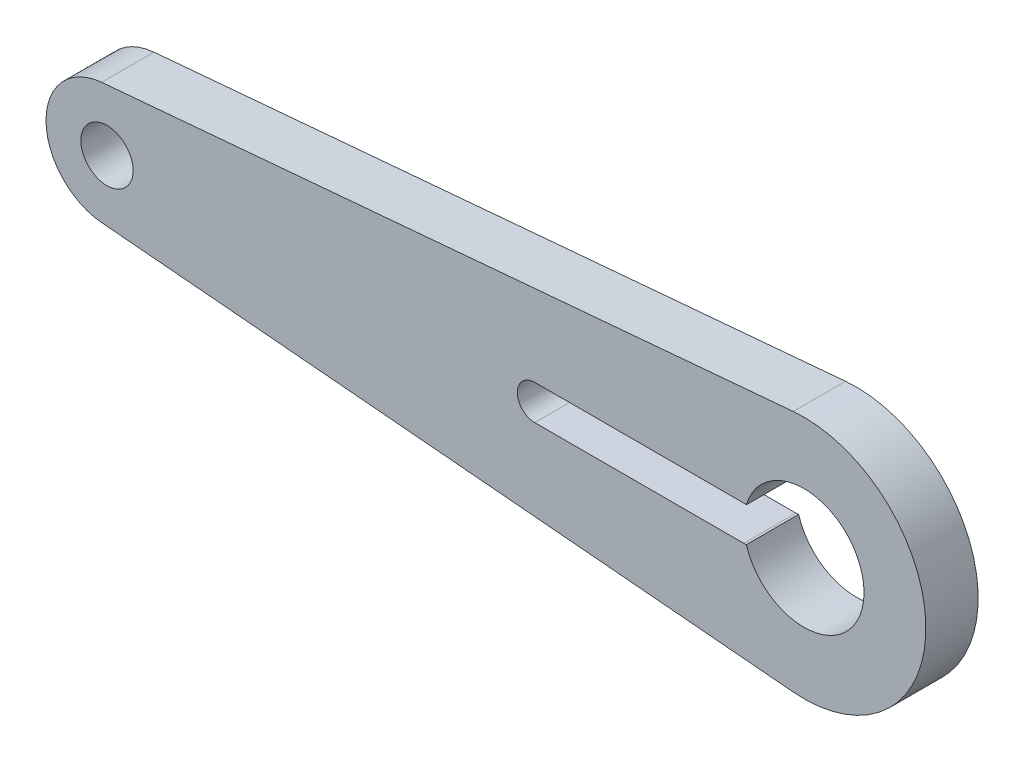
SolidWorks part; units mm, degrees
ref_plane "Front Plane" through (0, 0, 0) normal (0, 0, 1) x (1, 0, 0)
ref_plane "Top Plane" through (0, 0, 0) normal (0, 1, 0) x (1, 0, 0)
ref_plane "Right Plane" through (0, 0, 0) normal (1, 0, 0) x (0, 0, -1)
sketch "Sketch1" plane through (0, 0, 0) normal (0, 0, 1) x (1, 0, 0)
  line L0 (-40.3062, 3.4866) -> (-0.6125, 6.9732)
  line L1 (-40, 0) -> (0, 0) construction
  line L2 (-40.3062, -3.4866) -> (-0.6125, -6.9732)
  line L3 (-3.45, 0) -> (-15.45, 0) construction
  line L4 (-3.45, -1) -> (-15.45, -1)
  line L5 (-3.45, 1) -> (-15.45, 1)
  arc A0 (-0.6125, -6.9732) -> (-0.6125, 6.9732) centre (0, 0) ccw
  circle A1 centre (-40, 0) radius 1.5
  arc A2 (-40.3062, 3.4866) -> (-40.3062, -3.4866) centre (-40, 0) ccw
  circle A3 centre (0, 0) radius 3.45
  circle A4 centre (-40, 0) radius 3.5 construction
  circle A5 centre (0, 0) radius 7 construction
  arc A6 (-3.45, -1) -> (-3.45, 1) centre (-3.45, 0) ccw
  arc A7 (-15.45, 1) -> (-15.45, -1) centre (-15.45, 0) ccw
  point P15 (-9.45, 0)
  dimension "D1" = 14
  dimension "D2" = 3
  dimension "D5" = 40
  dimension "D6" = 2
  dimension "D7" = 12
  dimension "D3" = 2
  dimension "D4" = 3.55
extrude "Boss-Extrude1" add sketch "Sketch1" along normal blind 3 contours L0 A2 L2 A0 A7 L5 A6 A3 L4 A1
